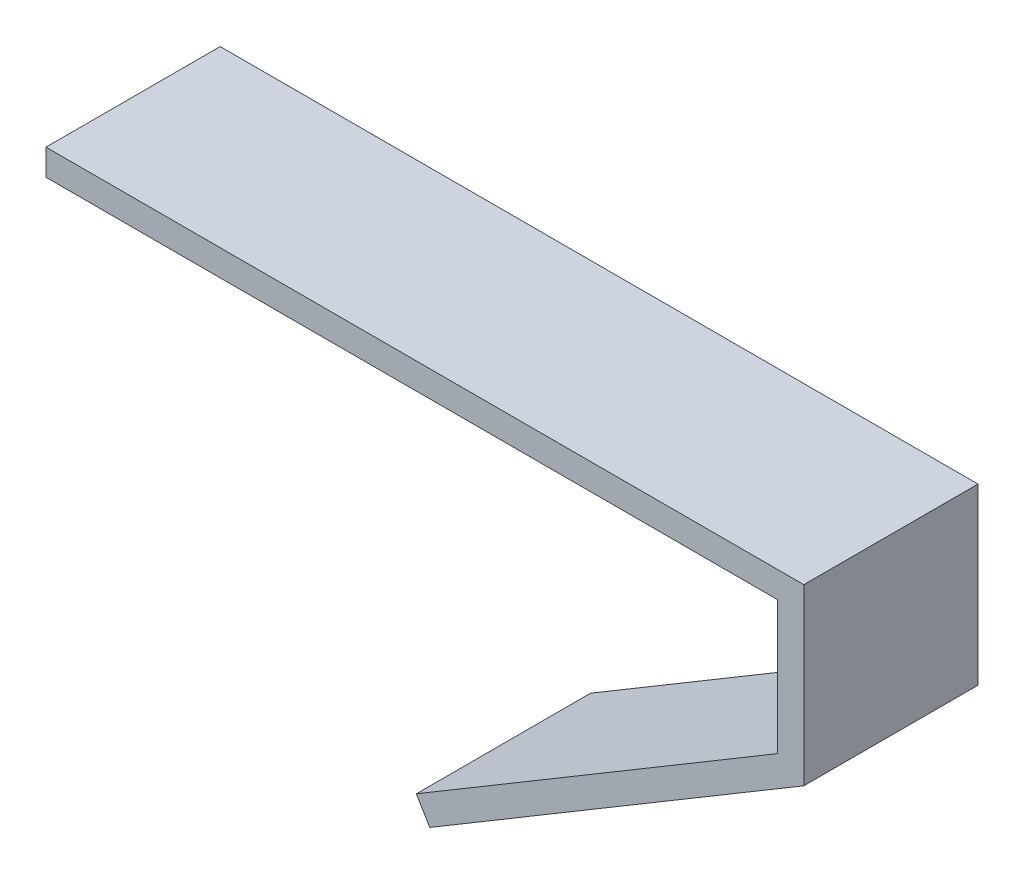
SolidWorks part; units mm, degrees
ref_plane "Front Plane" through (0, 0, 0) normal (0, 0, 1) x (1, 0, 0)
ref_plane "Top Plane" through (0, 0, 0) normal (0, 1, 0) x (1, 0, 0)
ref_plane "Right Plane" through (0, 0, 0) normal (1, 0, 0) x (0, 0, -1)
sketch "Sketch1" plane through (0, 0, 0) normal (0, 1, 0) x (1, 0, 0)
  line L0 (-86.6457, 0) -> (149.3256, 0) construction
  line L1 (-55, 0) -> (55, 0) construction
  line L2 (88.8579, 0) -> (88.8579, -74.8471) construction
ref_plane "Plane1" through (23.3111, -39.0893, 0) normal (-0.5122, 0.8589, 0) x (0, 0, 1)
sketch "Sketch2" plane through (23.3111, -39.0893, 0) normal (-0.5122, 0.8589, 0) x (0, 0, 1)
  line L1 (28.0347, 87.6783) -> (8.0347, 87.6783)
  line L2 (28.0347, 87.6783) -> (28.0347, 37.6783)
  line L3 (28.0347, 37.6783) -> (8.0347, 37.6783)
  line L4 (8.0347, 87.6783) -> (8.0347, 37.6783)
  line L5 (28.0347, 87.6783) -> (8.0347, 37.6783) construction
  line L6 (28.0347, 37.6783) -> (8.0347, 87.6783) construction
  point P0 (18.0347, 62.6783)
  dimension "D1" = 20
  dimension "D2" = 50
extrude "Boss-Extrude1" add sketch "Sketch2" along normal blind 3
sketch "Sketch3" plane through (0, 0, 28.0347) normal (0, 0, 1) x (1, 0, 0)
  line L1 (98.6154, 5.8189) -> (95.6154, 5.8189)
  line L2 (98.6154, 5.8189) -> (98.6154, 25.8189)
  line L3 (98.6154, 25.8189) -> (95.6154, 25.8189)
  line L4 (95.6154, 5.8189) -> (95.6154, 25.8189)
  dimension "D1" = 20
  dimension "D2" = 3
extrude "Boss-Extrude2" add sketch "Sketch3" against normal up to vertex (20 mm away)
sketch "Sketch4" plane through (95.6154, 0, 0) normal (-1, 0, 0) x (0, 0, 1)
  line L0 (28.0347, 25.8189) -> (28.0347, 7.5228) construction
  line L1 (8.0347, 25.8189) -> (28.0347, 25.8189)
  line L2 (8.0347, 25.8189) -> (8.0347, 22.8189)
  line L3 (8.0347, 22.8189) -> (28.0347, 22.8189)
  line L4 (28.0347, 25.8189) -> (28.0347, 22.8189)
  dimension "D1" = 3
extrude "Boss-Extrude3" add sketch "Sketch4" along normal blind 84
